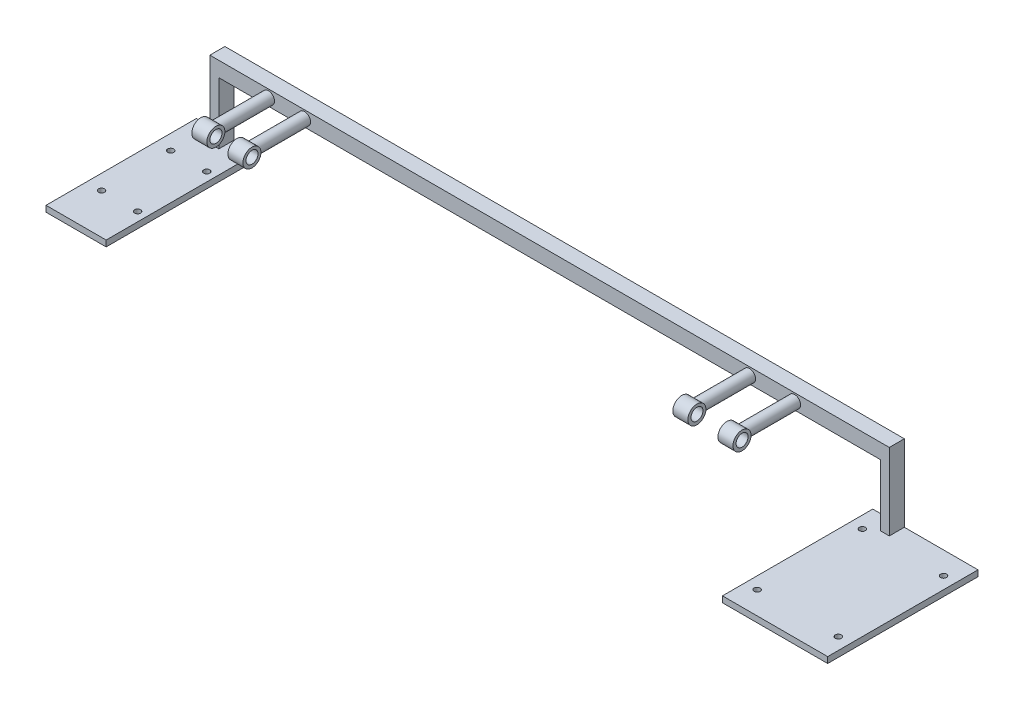
SolidWorks part; units mm, degrees
ref_plane "Front Plane" through (0, 0, 0) normal (0, 0, 1) x (1, 0, 0)
ref_plane "Top Plane" through (0, 0, 0) normal (0, 1, 0) x (1, 0, 0)
ref_plane "Right Plane" through (0, 0, 0) normal (1, 0, 0) x (0, 0, -1)
sketch "Sketch1" plane through (0, 0, 0) normal (0, 0, 1) x (1, 0, 0)
  line L0 (-1130, 0) -> (1130, 0)
  line L1 (-1130, 0) -> (-1130, -255)
  line L2 (-1130, -255) -> (-1100, -255)
  line L3 (-1100, -255) -> (-1100, -50)
  line L4 (-1100, -50) -> (1100, -50)
  line L5 (1100, -50) -> (1100, -255)
  line L6 (1100, -255) -> (1130, -255)
  line L7 (1130, -255) -> (1130, 0)
  line L8 (0, 374.8951) -> (0, -374.8951) construction
  point P4 (0, 0)
  point P13 (0, 0)
  dimension "D1" = 2260
  dimension "D2" = 255
  dimension "D3" = 50
  dimension "D4" = 30
extrude "Boss-Extrude1" add sketch "Sketch1" along normal blind 50
sketch "Sketch2" plane through (0, 0, 0) normal (0, 0, 1) x (1, 0, 0)
  line L0 (-1130, -255) -> (-1100, -255) construction
  line L1 (-1225, -255) -> (-1025, -255)
  line L2 (-1225, -255) -> (-1225, -275)
  line L3 (-1225, -275) -> (-1025, -275)
  line L4 (-1025, -255) -> (-1025, -275)
  line L6 (-1130, 0) -> (-1130, -255) construction
  dimension "D1" = 20
  dimension "D2" = 200
  dimension "D3" = 105
extrude "Boss-Extrude2" add sketch "Sketch2" along normal blind 500
sketch "Sketch4" plane through (0, 0, 50) normal (0, 0, 1) x (1, 0, 0)
  line L0 (-1025, -275) -> (-1025, -255) construction
  line L1 (1130, 0) -> (-1130, 0) construction
  circle A0 centre (-935, -25) radius 20
  dimension "D1" = 40
  dimension "D2" = 90
  dimension "D3" = 25
extrude "Boss-Extrude3" add sketch "Sketch4" along normal blind 200
sketch "Sketch5" plane through (0, 0, 250) normal (0, 0, 1) x (1, 0, 0)
  line L0 (-935, -25) -> (-935, -45) construction
  circle A0 centre (-935, -25) radius 20 construction
ref_plane "Plane1" through (-935, 0, 0) normal (-1, 0, 0) x (0, -1, 0)
sketch "Sketch6" plane through (-935, 0, 0) normal (-1, 0, 0) x (0, -1, 0)
  line L0 (25, 250) -> (45, 250) construction
  circle A0 centre (25, 250) radius 30
  circle A1 centre (25, 250) radius 12
  dimension "D1" = 60
  dimension "D2" = 24
extrude "Boss-Extrude4" add sketch "Sketch6" along normal mid plane 50
sketch "Sketch8" plane through (0, 0, 0) normal (0, 0, -1) x (-1, 0, 0)
  line L1 (-1375, -255) -> (-1025, -255)
  line L2 (-1375, -255) -> (-1375, -275)
  line L3 (-1375, -275) -> (-1025, -275)
  line L4 (-1025, -255) -> (-1025, -275)
  line L5 (-1100, -255) -> (-1130, -255) construction
  line L6 (-1130, -255) -> (-1130, 0) construction
  dimension "D1" = 105
  dimension "D2" = 350
  dimension "D3" = 20
extrude "Boss-Extrude5" add sketch "Sketch8" against normal blind 500
sketch "Sketch9" plane through (-910, 0, 0) normal (1, 0, 0) x (0, 0, -1)
  circle A0 centre (-249.7076, -24.2141) radius 20
  dimension "D1" = 40
extrude "Cut-Extrude1" cut sketch "Sketch9" against normal through all
pattern_linear "LPattern2" count 2 spacing 1750 along (1, 0, 0) of "Boss-Extrude3", "Boss-Extrude4", "Cut-Extrude1"
pattern_linear "LPattern4" count 2 spacing 120 along (1, 0, 0) of "Boss-Extrude4", "Cut-Extrude1", "Boss-Extrude3"
pattern_linear "LPattern5" count 2 spacing 1600 along (1, 0, 0) of "Boss-Extrude3", "Boss-Extrude4", "Cut-Extrude1"
sketch "Sketch10" plane through (0, -255, 0) normal (0, 1, 0) x (1, 0, 0)
  line L0 (1025, -500) -> (1025, 0) construction
  line L1 (1025, -500) -> (1375, -500) construction
  line L2 (-1025, -500) -> (-1225, -500) construction
  line L3 (-1025, -500) -> (-1025, 0) construction
  circle A0 centre (1065, -424.7076) radius 10
  circle A1 centre (1065, -74.7076) radius 10
  circle A2 centre (1335, -424.7076) radius 10
  circle A3 centre (1335, -74.7076) radius 10
  circle A4 centre (-1175, -365.2924) radius 10
  circle A5 centre (-1055, -365.2924) radius 10
  circle A6 centre (-1175, -135.2924) radius 10
  circle A7 centre (-1055, -135.2924) radius 10
  dimension "D1" = 20
  dimension "D6" = 20
  dimension "D2" = 270
  dimension "D3" = 40
  dimension "D4" = 75.2924
  dimension "D5" = 350
  dimension "D7" = 134.7076
  dimension "D8" = 30
  dimension "D9" = 120
  dimension "D10" = 230
extrude "Cut-Extrude2" cut sketch "Sketch10" against normal up to next
sketch "Sketch11" plane through (0, 0, 0) normal (0, 0, -1) x (-1, 0, 0)
  line L0 (1100, -50) -> (-1100, -50) construction
  line L1 (1130, 0) -> (1130, -255) construction
  circle A0 centre (-100, -25) radius 10
  dimension "D1" = 20
  dimension "D2" = 25
  dimension "D3" = 1230
extrude "Cut-Extrude3" cut sketch "Sketch11" against normal blind 40
cosmetic thread "Cosmetic Thread1" parameters "D2"=21
